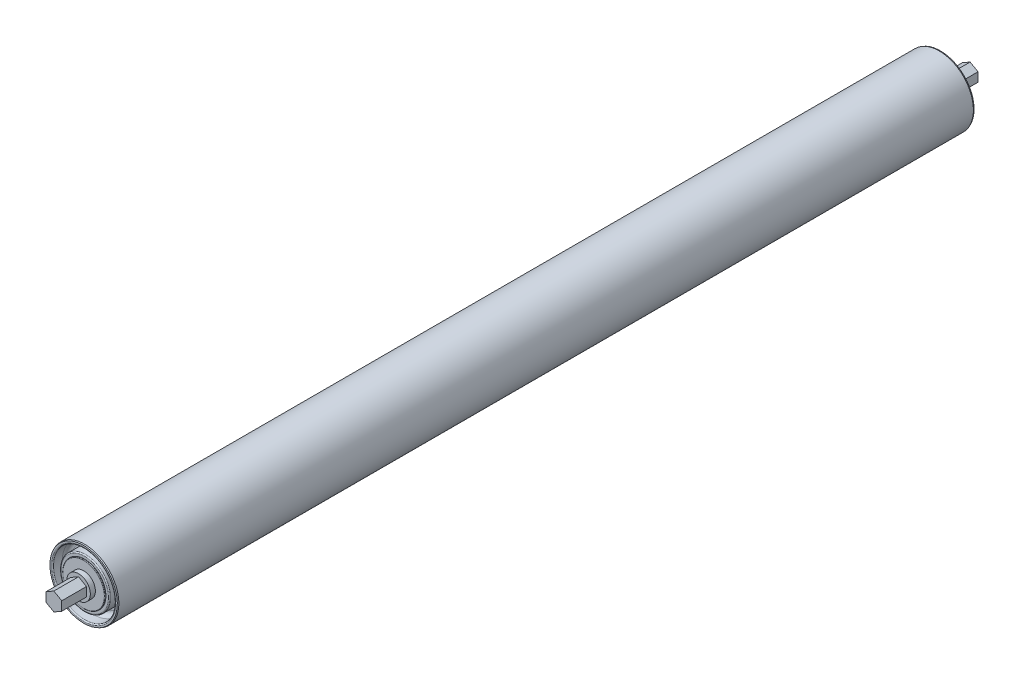
SolidWorks part; units mm, degrees
ref_plane "Front Plane" through (0, 0, 0) normal (0, 0, 1) x (1, 0, 0)
ref_plane "Top Plane" through (0, 0, 0) normal (0, 1, 0) x (1, 0, 0)
ref_plane "Right Plane" through (0, 0, 0) normal (1, 0, 0) x (0, 0, -1)
sketch "Sketch1" plane through (0, 0, 0) normal (1, 0, 0) x (0, 0, -1)
  line L0 (-323.85, 0) -> (323.85, 0) construction
  line L1 (-302.0219, 24.13) -> (302.0219, 24.13)
  line L2 (0, 24.13) -> (0, 0) construction
  line L3 (-323.85, 0) -> (-323.85, 5.5562)
  line L4 (-323.85, 5.5562) -> (-302.0219, 5.5562)
  line L5 (-307.975, 5.5562) -> (-307.975, -5.5562) construction
  line L6 (307.975, 5.5562) -> (307.975, -5.5562) construction
  line L7 (-307.975, -5.5562) -> (307.975, -5.5562) construction
  line L8 (-302.0219, 24.13) -> (-302.0219, 0) construction
  line L9 (-306.3875, 8.3344) -> (-306.3875, 0)
  line L10 (-306.3875, 8.3344) -> (-302.0219, 8.3344)
  line L11 (306.3875, 8.3344) -> (302.0219, 8.3344)
  line L12 (306.3875, 8.3344) -> (306.3875, 0)
  line L13 (323.85, 5.5563) -> (302.0219, 5.5563)
  line L14 (323.85, 0) -> (323.85, 5.5563)
  line L15 (-302.8156, 15.0019) -> (-302.0536, 15.0019) construction
  line L16 (-302.0219, 24.13) -> (-302.8156, 23.8125)
  line L17 (-302.8156, 23.8125) -> (-302.8156, 8.3344)
  line L18 (302.0219, 24.13) -> (302.8156, 23.8125)
  line L19 (302.8156, 23.8125) -> (302.8156, 8.3344)
  line L20 (-302.0536, 15.0019) -> (-302.0536, 17.5022) construction
  line L22 (-302.0536, 17.5022) -> (-292.8937, 17.5022) construction
  line L23 (-292.8937, 17.5022) -> (-292.8937, 21.971) construction
  line L24 (-292.8937, 21.971) -> (-302.8156, 21.971) construction
  arc A1 (-295.9417, 21.971) -> (-292.8937, 18.923) centre (-295.9417, 18.923) cw construction
  arc A2 (-302.8156, 22.733) -> (-302.0536, 21.971) centre (-302.0536, 22.733) ccw construction
  arc A3 (-302.0536, 16.7402) -> (-301.2916, 17.5022) centre (-301.2916, 16.7402) cw construction
  arc A4 (-302.8156, 14.6209) -> (-302.4346, 15.0019) centre (-302.4346, 14.6209) cw construction
  point P11 (-307.975, 0)
  point P12 (307.975, 0)
  point P13 (0, -5.5562)
  point P24 (-278.13, 0)
  point P27 (278.13, 0)
  point P32 (-292.8937, 19.7366)
  dimension "D14" = 3.048
  dimension "D15" = 0.762
  dimension "D16" = 0.381
  dimension "Overall Width" = 647.7
  dimension "Rollar Diameter" = 48.26
  dimension "Hex Axle Size" = 11.1125
  dimension "BF" = 615.95
  dimension "D2" = 16.6687
  dimension "D1" = 1.5875
  dimension "D5" = 15.875
  dimension "D6" = 45.72
  dimension "D7" = 45.72
  dimension "D3" = 4.3656
  dimension "D8" = 47.625
  dimension "D10" = 0.762
  dimension "D9" = 35.0044
  dimension "D11" = 30.0038
  dimension "D12" = 43.942
  dimension "D13" = 13.4937
  dimension "Rollar Width" = 605.6312
sketch "Sketch5" plane through (0, 0, 0) normal (0, 0, 1) x (1, 0, 0)
  circle A0 centre (0, 0) radius 24.13
  dimension "D1" = 48.26
sketch "Sketch3" plane through (0, 0, 0) normal (1, 0, 0) x (0, 0, -1)
  line L0 (323.85, 5.5563) -> (302.0219, 5.5563) construction
  line L1 (323.85, 0) -> (323.85, 5.5563) construction
  line L2 (-323.85, 0) -> (-323.85, 5.5562) construction
  line L3 (-323.85, 5.5562) -> (-302.0219, 5.5562) construction
  line L4 (302.8156, 23.8125) -> (302.8156, 8.3344) construction
  line L5 (302.0219, 24.13) -> (302.8156, 23.8125) construction
  line L6 (-302.0219, 24.13) -> (302.0219, 24.13) construction
  line L7 (-302.0219, 24.13) -> (-302.8156, 23.8125) construction
  line L8 (-302.8156, 23.8125) -> (-302.8156, 8.3344) construction
  line L9 (306.3875, 8.3344) -> (302.0219, 8.3344) construction
  line L10 (306.3875, 8.3344) -> (306.3875, 0) construction
  line L11 (-306.3875, 8.3344) -> (-306.3875, 0) construction
  line L12 (-306.3875, 8.3344) -> (-302.0219, 8.3344) construction
  line L13 (323.85, 5.5563) -> (306.3875, 5.5563)
  line L14 (323.85, 0) -> (323.85, 5.5563)
  line L15 (-323.85, 0) -> (-323.85, 5.5562)
  line L16 (-323.85, 5.5562) -> (-306.3875, 5.5562)
  line L17 (302.8156, 23.8125) -> (302.8156, 8.3344)
  line L18 (302.0219, 24.13) -> (302.8156, 23.8125)
  line L19 (-302.0219, 24.13) -> (302.0219, 24.13)
  line L20 (-302.0219, 24.13) -> (-302.8156, 23.8125)
  line L21 (-302.8156, 23.8125) -> (-302.8156, 8.3344)
  line L22 (306.3875, 8.3344) -> (302.8156, 8.3344)
  line L23 (306.3875, 8.3344) -> (306.3875, 5.5563)
  line L24 (-306.3875, 8.3344) -> (-306.3875, 5.5562)
  line L25 (-306.3875, 8.3344) -> (-302.8156, 8.3344)
  line L26 (-323.85, 0) -> (323.85, 0)
revolve "Revolve1" add sketch "Sketch3" angle 360 about L0
sketch "Sketch4" plane through (0, 0, 323.85) normal (0, 0, 1) x (1, 0, 0)
  line L1 (0, 6.4158) -> (-5.5562, 3.2079)
  line L2 (-5.5562, 3.2079) -> (-5.5562, -3.2079)
  line L3 (-5.5562, -3.2079) -> (0, -6.4158)
  line L4 (0, -6.4158) -> (5.5562, -3.2079)
  line L5 (5.5562, -3.2079) -> (5.5562, 3.2079)
  line L6 (5.5562, 3.2079) -> (0, 6.4158)
  circle A0 centre (0, 0) radius 5.5562 construction
extrude "Boss-Extrude1" add sketch "Sketch4" against normal up to surface (647.7 mm away) up to face at (0, -5.5562, -323.85)
sketch "Sketch6" plane through (0, 0, 0) normal (1, 0, 0) x (0, 0, -1)
  line L0 (-292.8937, 21.971) -> (-302.8156, 21.971) construction
  line L1 (-292.8937, 17.5022) -> (-292.8937, 21.971) construction
  line L2 (-302.0536, 17.5022) -> (-292.8937, 17.5022) construction
  line L3 (-302.0536, 15.0019) -> (-302.0536, 17.5022) construction
  line L4 (-302.8156, 15.0019) -> (-302.0536, 15.0019) construction
  line L5 (-295.9417, 21.971) -> (-302.0536, 21.971)
  line L6 (-292.8937, 17.5022) -> (-292.8937, 18.923)
  line L7 (-301.2916, 17.5022) -> (-292.8937, 17.5022)
  line L8 (-302.0536, 15.0019) -> (-302.0536, 16.7402)
  line L9 (-302.4346, 15.0019) -> (-302.0536, 15.0019)
  line L10 (-302.8156, 22.733) -> (-302.8156, 14.6209)
  arc A0 (-302.8156, 22.733) -> (-302.0536, 21.971) centre (-302.0536, 22.733) ccw construction
  arc A1 (-292.8937, 18.923) -> (-295.9417, 21.971) centre (-295.9417, 18.923) ccw construction
  arc A2 (-301.2916, 17.5022) -> (-302.0536, 16.7402) centre (-301.2916, 16.7402) ccw construction
  arc A3 (-302.4346, 15.0019) -> (-302.8156, 14.6209) centre (-302.4346, 14.6209) ccw construction
  arc A4 (-302.8156, 22.733) -> (-302.0536, 21.971) centre (-302.0536, 22.733) ccw
  arc A5 (-292.8937, 18.923) -> (-295.9417, 21.971) centre (-295.9417, 18.923) ccw
  arc A6 (-301.2916, 17.5022) -> (-302.0536, 16.7402) centre (-301.2916, 16.7402) ccw
  arc A7 (-302.4346, 15.0019) -> (-302.8156, 14.6209) centre (-302.4346, 14.6209) ccw
revolve "Cut-Revolve1" cut sketch "Sketch6" angle 360 about L0
mirror "Mirror2" about plane through (0, 0, 0) normal (0, 0, 1) of "Cut-Revolve1"
ref_plane "Contact Plane 1" through (0, 24.13, 0) normal (0, 1, 0) x (1, 0, 0)
equation "\"D2@Sketch1\"=\"Hex Axle Size@Sketch1\"*1.5"
equation "\"D7@Sketch1\"=\"D6@Sketch1\""
equation "\"D9@Sketch1\"=\"D2@Sketch1\"*2.1"
equation "\"D11@Sketch1\"=\"D2@Sketch1\"*1.8"
equation "\"D12@Sketch1\"=1.7+\"D10@Sketch1\""
equation "\"D16@Sketch1\"=\"D15@Sketch1\"/2"
